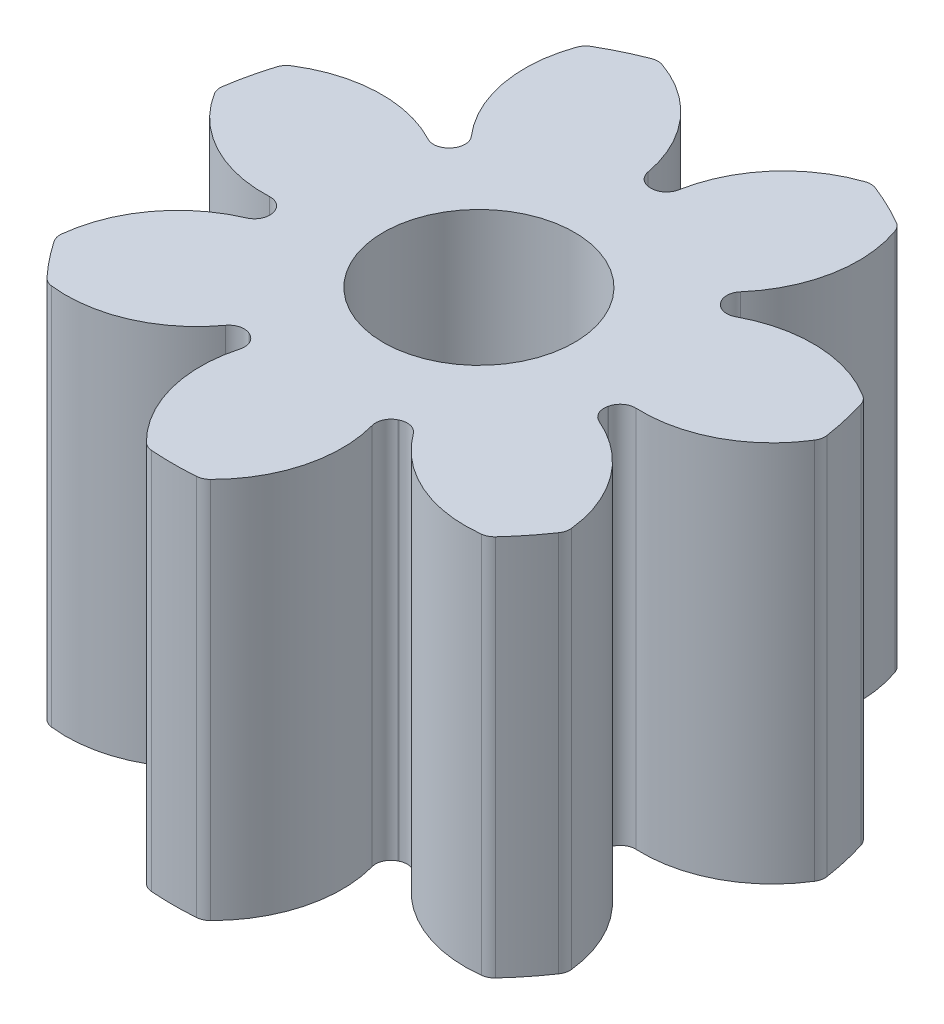
SolidWorks part; units mm, degrees
ref_plane "Front Plane" through (0, 0, 0) normal (0, 0, 1) x (1, 0, 0)
ref_plane "Top Plane" through (0, 0, 0) normal (0, 1, 0) x (1, 0, 0)
ref_plane "Right Plane" through (0, 0, 0) normal (1, 0, 0) x (0, 0, -1)
sketch "Sketch1" plane through (0, 0, 0) normal (0, 1, 0) x (1, 0, 0)
  circle A0 centre (0, 0) radius 2
  circle A1 centre (0, 0) radius 0.625
  dimension "D1" = 4
  dimension "D2" = 1.25
extrude "Boss-Extrude1" add sketch "Sketch1" along normal blind 2.5
sketch "Sketch2" plane through (0, 2.5, 0) normal (0, 1, 0) x (1, 0, 0)
  line L0 (0, 0) -> (0, 2.1618) construction
  line L1 (0, 0) -> (0.9468, 1.9661) construction
  line L2 (-0.3894, 1.7061) -> (0.3894, 1.7061) construction
  line L3 (0.3894, 1.7061) -> (1.0911, 1.3682) construction
  line L4 (-0.5472, 2.469) -> (0, 0.9656) construction
  line L5 (0, 0) -> (-0.0895, 1.1214) construction
  circle A0 centre (0, 0) radius 1.125 construction
  circle A1 centre (0, 0) radius 1.75 construction
  circle A2 centre (0, 0) radius 2 construction
  circle A3 centre (0, 0) radius 2 construction
  arc A4 (-0.6996, 1.8736) -> (-0.0895, 1.1214) centre (-0.9423, 1.0533) cw
  arc A5 (0.6996, 1.8736) -> (0.0895, 1.1214) centre (0.9423, 1.0533) ccw
  arc A6 (-0.6996, 1.8736) -> (0.6996, 1.8736) centre (0, 0) cw
  arc A7 (-0.0895, 1.1214) -> (0.0895, 1.1214) centre (0, 0) cw
  dimension "D1" = 3.5
  dimension "D2" = 2.25
  dimension "D3" = 25.714
  dimension "D4" = 20
extrude "Cut-Extrude1" cut sketch "Sketch2" against normal through all
pattern_circular "CirPattern1" count 7 over 360 about axis through (0, 0, 0) along (0, 1, 0) of "Cut-Extrude1"
fillet "Fillet1" radius 0.1 28 edges at (-0.9326, 1.25, -0.6292) (-1.1132, 1.25, 0.1622) (-1.9011, 1.25, -0.6212) (-1.9823, 1.25, -0.2651) (1.9823, 1.25, -0.2651) (0.0895, 1.25, -1.1214) (-0.0895, 1.25, -1.1214) (0.9326, 1.25, -0.6292) (0.8209, 1.25, -0.7692) (1.0734, 1.25, 0.3368) (0.4059, 1.25, 1.0492) (1.1132, 1.25, 0.1622) (1.671, 1.25, 1.099) (1.4433, 1.25, 1.3846) (0.5673, 1.25, 0.9715) (0.1826, 1.25, 1.9916) (-0.5673, 1.25, 0.9715) (-1.4433, 1.25, 1.3846) (-0.1826, 1.25, 1.9916) (-0.4059, 1.25, 1.0492) (-0.8209, 1.25, -0.7692) (-1.0734, 1.25, 0.3368) (-1.671, 1.25, 1.099) (1.9011, 1.25, -0.6212) (1.0287, 1.25, -1.7152) (0.6996, 1.25, -1.8736) (-0.6996, 1.25, -1.8736) (-1.0287, 1.25, -1.7152)
